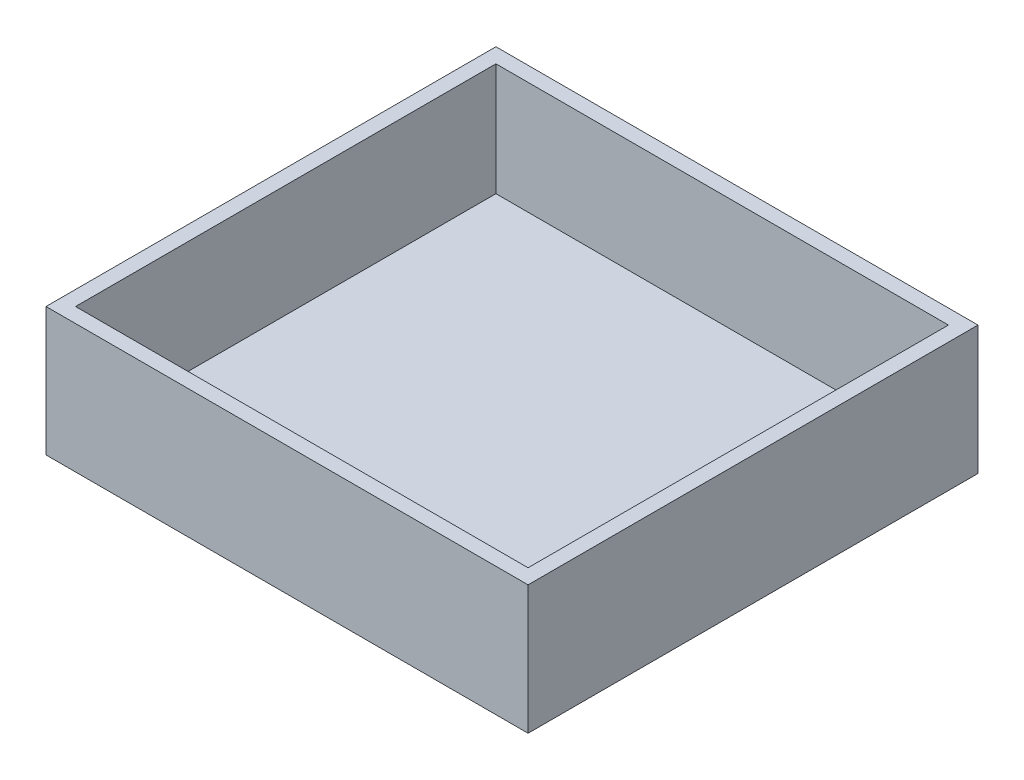
SolidWorks part; units mm, degrees
ref_plane "Front Plane" through (0, 0, 0) normal (0, 0, 1) x (1, 0, 0)
ref_plane "Top Plane" through (0, 0, 0) normal (0, 1, 0) x (1, 0, 0)
ref_plane "Right Plane" through (0, 0, 0) normal (1, 0, 0) x (0, 0, -1)
sketch "Sketch1" plane through (0, 0, 0) normal (0, 1, 0) x (1, 0, 0)
  line L1 (-95.25, -88.9) -> (95.25, -88.9)
  line L2 (-95.25, -88.9) -> (-95.25, 88.9)
  line L3 (-95.25, 88.9) -> (95.25, 88.9)
  line L4 (95.25, -88.9) -> (95.25, 88.9)
  line L5 (-95.25, -88.9) -> (95.25, 88.9) construction
  line L6 (-95.25, 88.9) -> (95.25, -88.9) construction
  point P0 (0, 0)
  dimension "D1" = 190.5
  dimension "D2" = 177.8
extrude "Boss-Extrude1" add sketch "Sketch1" along normal blind 50.8 contours L1 L4 L3 L2
sketch "Sketch2" plane through (0, 50.8, 0) normal (0, 1, 0) x (1, 0, 0)
  line L1 (-89.408, -83.058) -> (89.408, -83.058)
  line L2 (-89.408, -83.058) -> (-89.408, 83.058)
  line L3 (-89.408, 83.058) -> (89.408, 83.058)
  line L4 (89.408, -83.058) -> (89.408, 83.058)
  line L5 (-89.408, -83.058) -> (89.408, 83.058) construction
  line L6 (-89.408, 83.058) -> (89.408, -83.058) construction
  point P0 (0, 0)
  dimension "D1" = 166.116
  dimension "D2" = 178.816
extrude "Cut-Extrude1" cut sketch "Sketch2" against normal blind 44.45
